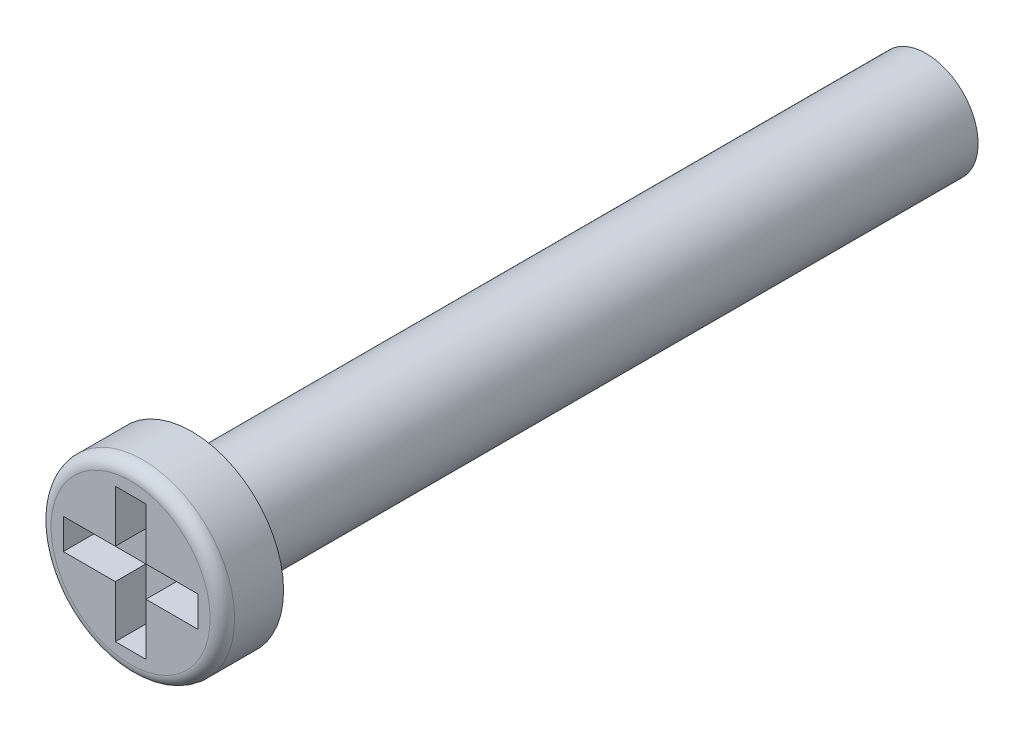
SolidWorks part; units mm, degrees
ref_plane "Front Plane" through (0, 0, 0) normal (0, 0, 1) x (1, 0, 0)
ref_plane "Top Plane" through (0, 0, 0) normal (0, 1, 0) x (1, 0, 0)
ref_plane "Right Plane" through (0, 0, 0) normal (1, 0, 0) x (0, 0, -1)
sketch "Sketch1" plane through (0, 0, 0) normal (0, 0, 1) x (1, 0, 0)
  circle A0 centre (0, 0) radius 1.5
  dimension "D1" = 3
extrude "Boss-Extrude1" add sketch "Sketch1" along normal blind 1
sketch "Sketch2" plane through (0, 0, 0) normal (0, 0, -1) x (-1, 0, 0)
  circle A0 centre (0, 0) radius 0.85
  dimension "D1" = 1.7
extrude "Boss-Extrude2" add sketch "Sketch2" along normal blind 12
sketch "Sketch3" plane through (0, 0, 1) normal (0, 0, 1) x (1, 0, 0)
  line L0 (-0.25, 1.1) -> (-0.25, 0.25)
  line L1 (-0.25, 1.1) -> (0.25, 1.1)
  line L3 (-0.25, -1.1) -> (0.25, -1.1)
  line L5 (0, -1.1) -> (0, 1.1) construction
  line L6 (-0.25, 0) -> (0.25, 0) construction
  line L8 (-1.1, 0.25) -> (-1.1, -0.25)
  line L10 (1.1, 0.25) -> (1.1, -0.25)
  line L11 (0, -0.25) -> (0, 0.25) construction
  line L12 (-1.1, 0) -> (1.1, 0) construction
  line L13 (-0.25, -1.1) -> (-0.25, -0.25)
  line L14 (0.25, 1.1) -> (0.25, 0.25)
  line L15 (0.25, -1.1) -> (0.25, -0.25)
  line L16 (-1.1, 0.25) -> (-0.25, 0.25)
  line L17 (0.25, 0.25) -> (1.1, 0.25)
  line L18 (-1.1, -0.25) -> (-0.25, -0.25)
  line L19 (0.25, -0.25) -> (1.1, -0.25)
  point P0 (0, 0)
  point P4 (0, 0)
  dimension "D1" = 2.2
  dimension "D2" = 0.5
  dimension "D3" = 0.5
  dimension "D4" = 2.2
extrude "Cut-Extrude1" cut sketch "Sketch3" against normal blind 0.5
fillet "Fillet1" radius 0.2 1 edges at (1.5, 0, 1)
